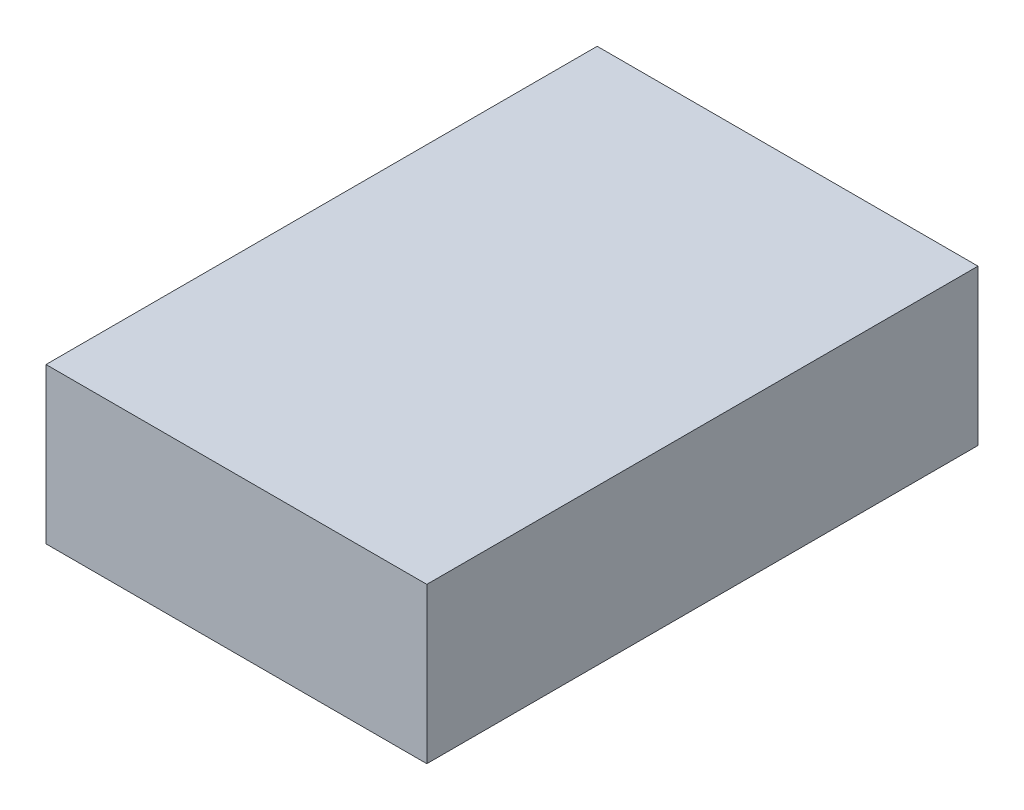
SolidWorks part; units mm, degrees
ref_plane "Front Plane" through (0, 0, 0) normal (0, 0, 1) x (1, 0, 0)
ref_plane "Top Plane" through (0, 0, 0) normal (0, 1, 0) x (1, 0, 0)
ref_plane "Right Plane" through (0, 0, 0) normal (1, 0, 0) x (0, 0, -1)
sketch "Sketch1" plane through (0, 0, 0) normal (0, 1, 0) x (1, 0, 0)
  line L5 (-19, -27.5) -> (19, -27.5)
  line L6 (-19, -27.5) -> (-19, 27.5)
  line L7 (-19, 27.5) -> (19, 27.5)
  line L8 (19, -27.5) -> (19, 27.5)
  line L9 (-19, -27.5) -> (19, 27.5) construction
  line L10 (-19, 27.5) -> (19, -27.5) construction
  point P0 (0, 0)
  dimension "D1" = 55
  dimension "D2" = 38
extrude "Boss-Extrude1" add sketch "Sketch1" along normal blind 15.5 contours L7 L8 L5 L6
equation "\"ph_length\"=1.38"
equation "\"ph_height\"=0.610236"
equation "\"D1@Boss-Extrude1\"=\"ph_height\""
